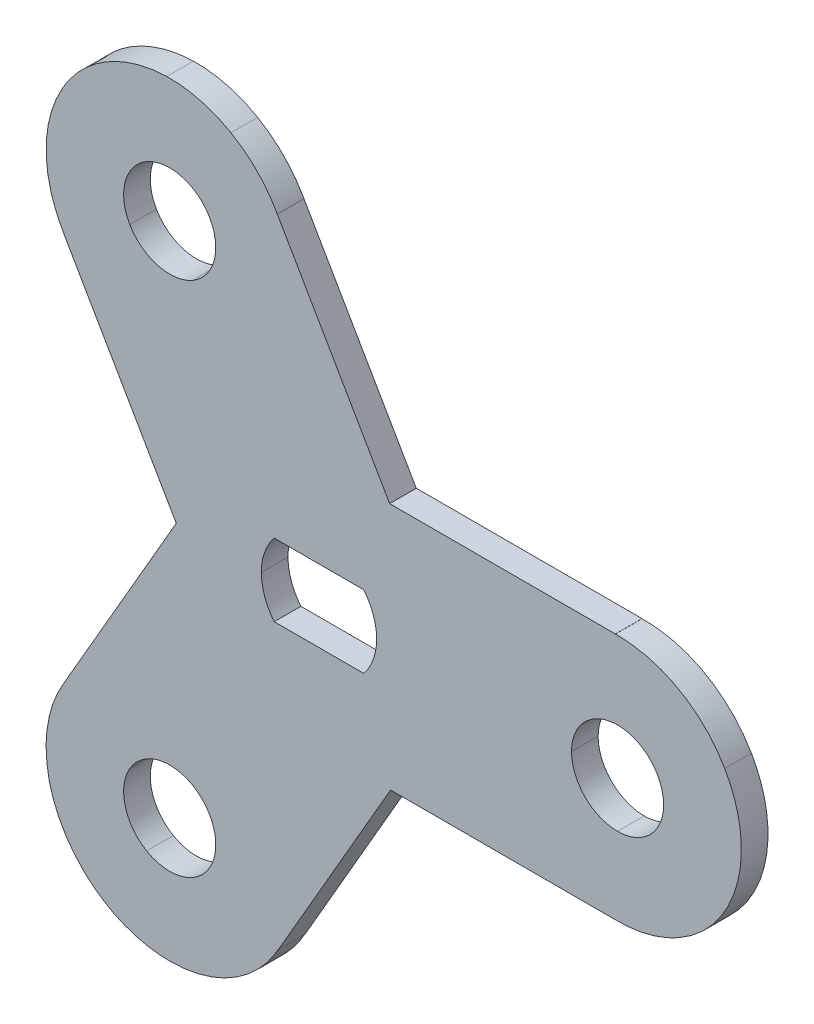
SolidWorks part; units mm, degrees
ref_plane "Front Plane" through (0, 0, 0) normal (0, 0, 1) x (1, 0, 0)
ref_plane "Top Plane" through (0, 0, 0) normal (0, 1, 0) x (1, 0, 0)
ref_plane "Right Plane" through (0, 0, 0) normal (1, 0, 0) x (0, 0, -1)
sketch "carrier" plane through (-89.6124, 67.4585, 0) normal (0, 0, 1) x (1, 0, 0)
  line L796 (118.819, 161.9893) -> (118.8102, 161.9805)
  line L797 (118.8102, 161.9805) -> (125.513, 150.383)
  line L798 (125.513, 150.383) -> (118.819, 138.7942)
  line L799 (118.819, 138.7942) -> (118.8102, 138.7766)
  line L801 (131.5719, 131.4123) -> (131.5807, 131.4035)
  line L802 (131.5807, 131.4035) -> (138.2835, 143.0099)
  line L803 (138.2835, 143.0099) -> (151.6538, 143.0099)
  line L804 (151.6538, 143.0099) -> (151.6714, 143.0099)
  line L806 (151.6714, 157.7472) -> (151.6714, 157.7548)
  line L807 (151.6714, 157.7548) -> (138.225, 157.7548)
  line L808 (138.225, 157.7548) -> (131.5398, 169.3348)
  line L809 (131.5398, 169.3348) -> (131.531, 169.3524)
  line L811 (131.3482, 148.2249) -> (136.684, 148.2249)
  line L813 (136.684, 152.5376) -> (131.3482, 152.5376)
  spline S1 degree 3 poles (124.9469, 173.1541) (122.467, 173.0886) (120.0788, 171.7725) (118.7485, 169.4682) knots 0.003756 0.003756 0.003756 0.003756 1 1 1 1
  spline S8 degree 3 poles (154.5471, 150.3813) (154.5471, 148.866) (153.3187, 147.6376) (151.8034, 147.6376) knots 0 0 0 0 1 1 1 1
  spline S9 degree 3 poles (151.8034, 147.6376) (150.2881, 147.6376) (149.0597, 148.866) (149.0597, 150.3813) knots 0 0 0 0 1 1 1 1
  spline S10 degree 3 poles (149.0597, 150.3813) (149.0597, 151.8966) (150.2881, 153.125) (151.8034, 153.125) knots 0 0 0 0 1 1 1 1
  spline S11 degree 3 poles (151.8034, 153.125) (153.3187, 153.125) (154.5471, 151.8966) (154.5471, 150.3813) knots 0 0 0 0 1 1 1 1
  spline S12 degree 3 poles (123.7501, 168.1621) (125.0624, 168.9197) (126.7404, 168.4701) (127.4981, 167.1578) knots 0 0 0 0 1 1 1 1
  spline S13 degree 3 poles (127.4981, 167.1578) (128.2557, 165.8455) (127.8061, 164.1675) (126.4938, 163.4099) knots 0 0 0 0 1 1 1 1
  spline S14 degree 3 poles (126.4938, 163.4099) (125.1815, 162.6522) (123.5035, 163.1018) (122.7459, 164.4141) knots 0 0 0 0 1 1 1 1
  spline S15 degree 3 poles (122.7459, 164.4141) (121.9882, 165.7264) (122.4378, 167.4044) (123.7501, 168.1621) knots 0 0 0 0 1 1 1 1
  spline S16 degree 3 poles (123.7501, 132.6005) (122.4378, 133.3581) (121.9882, 135.0361) (122.7459, 136.3484) knots 0 0 0 0 1 1 1 1
  spline S17 degree 3 poles (122.7459, 136.3484) (123.5035, 137.6607) (125.1815, 138.1103) (126.4938, 137.3527) knots 0 0 0 0 1 1 1 1
  spline S18 degree 3 poles (126.4938, 137.3527) (127.8061, 136.595) (128.2557, 134.917) (127.4981, 133.6047) knots 0 0 0 0 1 1 1 1
  spline S19 degree 3 poles (127.4981, 133.6047) (126.7404, 132.2924) (125.0624, 131.8428) (123.7501, 132.6005) knots 0 0 0 0 1 1 1 1
  spline S21 degree 3 poles (118.7485, 169.4682) (117.3603, 167.0639) (117.4832, 164.2113) (118.819, 161.9893) knots 0 0 0 0 1 1 1 1
  spline S22 degree 3 poles (118.8102, 138.7766) (118.1389, 137.6657) (117.7607, 136.368) (117.7607, 134.9754) knots 0 0 0 0 1 1 1 1
  spline S23 degree 3 poles (117.7607, 134.9754) (117.7607, 130.9057) (121.064, 127.6023) (125.1337, 127.6023) knots 0 0 0 0 1 1 1 1
  spline S24 degree 3 poles (125.1337, 127.6023) (127.91, 127.6023) (130.3156, 129.1445) (131.5719, 131.4123) knots 0 0 0 0 1 1 1 1
  spline S25 degree 3 poles (151.6714, 143.0099) (152.9691, 142.984) (154.2842, 143.3014) (155.4902, 143.9977) knots 0 0 0 0 1 1 1 1
  spline S26 degree 3 poles (155.4902, 143.9977) (159.0147, 146.0325) (160.2239, 150.545) (158.189, 154.0695) knots 0 0 0 0 1 1 1 1
  spline S27 degree 3 poles (158.189, 154.0695) (156.8009, 156.4738) (154.2636, 157.7931) (151.6714, 157.7472) knots 0 0 0 0 1 1 1 1
  spline S28 degree 3 poles (131.531, 169.3524) (130.9047, 170.4892) (129.9766, 171.4695) (128.7705, 172.1658) knots 0 0 0 0 1 1 1 1
  spline S29 degree 3 poles (128.7705, 172.1658) (127.5657, 172.8614) (126.2442, 173.1795) (124.9469, 173.1541) knots 0 0 0 0 0.994464 0.994464 0.994464 0.994464
  spline S30 degree 3 poles (131.3482, 152.5376) (130.8705, 151.9478) (130.5809, 151.2038) (130.5809, 150.3857) knots 0 0 0 0 1 1 1 1
  spline S31 degree 3 poles (130.5809, 150.3857) (130.5809, 149.5675) (130.8705, 148.8148) (131.3482, 148.2249) knots 0 0 0 0 1 1 1 1
  spline S32 degree 3 poles (136.684, 148.2249) (137.1616, 148.8148) (137.4513, 149.5675) (137.4513, 150.3857) knots 0 0 0 0 1 1 1 1
  spline S33 degree 3 poles (137.4513, 150.3857) (137.4513, 151.2038) (137.1616, 151.9478) (136.684, 152.5376) knots 0 0 0 0 1 1 1 1
extrude "Boss-Extrude5" add sketch "carrier" along normal blind 1.5875 separate body contours S15 S14 S13 S12 | S32 S33 L813 S30 S31 L811 | S11 S10 S9 S8 | S19 S18 S17 S16 | L797 L798 L799 S22 S23 S24 L801 L802 L803 L804 S25 S26 S27 L806 L807 L808 L809 S28 S29 S1 S21 L796
